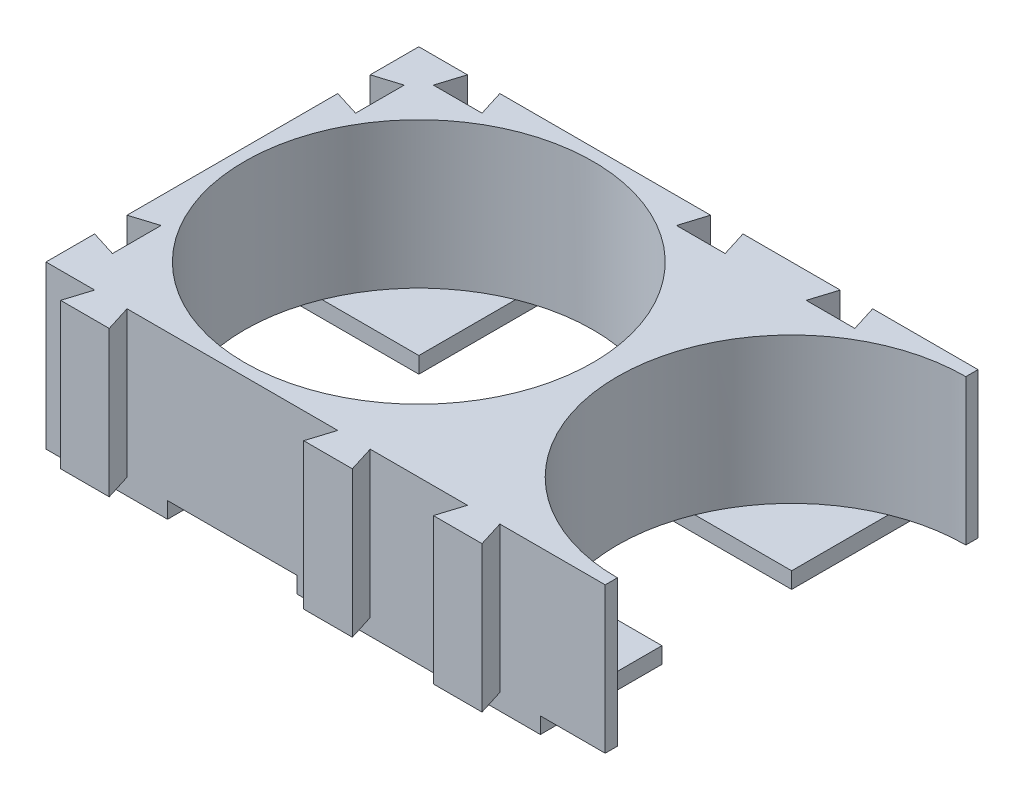
SolidWorks part; units mm, degrees
ref_plane "Front Plane" through (0, 0, 0) normal (0, 0, 1) x (1, 0, 0)
ref_plane "Top Plane" through (0, 0, 0) normal (0, 1, 0) x (1, 0, 0)
ref_plane "Right Plane" through (0, 0, 0) normal (1, 0, 0) x (0, 0, -1)
sketch "Sketch1" plane through (0, 0, 0) normal (0, 1, 0) x (1, 0, 0)
  line L1 (0, 0) -> (47.6, 0)
  line L2 (0, 0) -> (0, 24.6)
  line L3 (0, 24.6) -> (47.6, 24.6)
  line L4 (47.6, 0) -> (47.6, 24.6)
  dimension "D1" = 47.6
  dimension "D2" = 24.6
extrude "Boss-Extrude1" add sketch "Sketch1" along normal blind 10
sketch "Sketch2" plane through (0, 10, 0) normal (0, 1, 0) x (1, 0, 0)
  line L0 (0, -5.5) -> (0, 5.5) construction
  line L1 (47.6, 0) -> (47.6, 24.6) construction
  line L3 (47.6, 24.6) -> (0, 24.6) construction
  circle A0 centre (11.5, 13.1) radius 10.75
  circle A1 centre (34.5, 13.1) radius 10.75
  dimension "D1" = 21.5
  dimension "D2" = 21.5
  dimension "D3" = 23
  dimension "D4" = 11.5
  dimension "D5" = 13.1
  dimension "D6" = 11.5
extrude "Cut-Extrude1" cut sketch "Sketch2" against normal blind 9
sketch "Sketch3" plane through (0, 10, 0) normal (0, 1, 0) x (1, 0, 0)
  line L0 (0, 24.6) -> (0, -11.4) construction
  line L1 (0, -5.5) -> (0, 5.5) construction
  line L2 (47.6, 24.6) -> (0, 24.6) construction
  line L9 (3, 24.6) -> (2.5, 23)
  line L10 (2.5, 23) -> (5.5, 23)
  line L11 (5.5, 23) -> (5, 24.6)
  line L12 (5, 24.6) -> (3, 24.6)
  line L13 (18, 24.6) -> (17.5, 23)
  line L14 (17.5, 23) -> (20.5, 23)
  line L15 (20.5, 23) -> (20, 24.6)
  line L16 (20, 24.6) -> (18, 24.6)
  line L17 (26, 24.6) -> (25.5, 23)
  line L18 (25.5, 23) -> (28.5, 23)
  line L19 (28.5, 23) -> (28, 24.6)
  line L20 (28, 24.6) -> (26, 24.6)
  line L21 (41, 24.6) -> (40.5, 23)
  line L22 (40.5, 23) -> (43.5, 23)
  line L23 (43.5, 23) -> (43, 24.6)
  line L24 (43, 24.6) -> (41, 24.6)
  line L25 (0, 21.6) -> (1.6, 22.1)
  line L26 (1.6, 22.1) -> (1.6, 19.1)
  line L27 (1.6, 19.1) -> (0, 19.6)
  line L28 (0, 19.6) -> (0, 21.6)
  line L29 (0, 6.6) -> (1.6, 7.1)
  line L30 (1.6, 7.1) -> (1.6, 4.1)
  line L31 (1.6, 4.1) -> (0, 4.6)
  line L32 (0, 4.6) -> (0, 6.6)
  dimension "D1" = 2
  dimension "D2" = 3
  dimension "D3" = 0.5
  dimension "D4" = 1.6
  dimension "D5" = 3
  dimension "D6" = 13
  dimension "D7" = 2
  dimension "D8" = 3
  dimension "D9" = 0.5
  dimension "D10" = 1.6
  dimension "D11" = 6
  dimension "D12" = 2
  dimension "D13" = 3
  dimension "D14" = 0.5
  dimension "D15" = 1.6
  dimension "D16" = 13
  dimension "D17" = 2
  dimension "D18" = 3
  dimension "D19" = 0.5
  dimension "D20" = 1.6
  dimension "D21" = 3
  dimension "D22" = 2
  dimension "D23" = 0.5
  dimension "D24" = 1.6
  dimension "D25" = 3
  dimension "D26" = 3
  dimension "D27" = 2
  dimension "D28" = 0.5
  dimension "D29" = 1.6
  dimension "D30" = 13
extrude "Cut-Extrude2" cut sketch "Sketch3" against normal blind 9
sketch "Sketch5" plane through (0, 10, 0) normal (0, 1, 0) x (1, 0, 0)
  line L0 (-5.5, 0) -> (5.5, 0) construction
  line L1 (47.6, 24.6) -> (46, 24.6)
  line L2 (47.6, 24.6) -> (47.6, 0)
  line L3 (47.6, 0) -> (46, 0)
  line L4 (46, 24.6) -> (46, 0)
  dimension "D1" = 1.6
extrude "Cut-Extrude3" cut sketch "Sketch5" against normal blind 10
sketch "Sketch6" plane through (0, 10, 0) normal (0, 1, 0) x (1, 0, 0)
  line L0 (46, 24.6) -> (46, 0) construction
  line L1 (0, 0) -> (46, 0)
  line L2 (0, 0) -> (0, 1.6)
  line L3 (0, 1.6) -> (46, 1.6)
  line L4 (46, 0) -> (46, 1.6)
  dimension "D1" = 1.6
extrude "Cut-Extrude4" cut sketch "Sketch6" against normal blind 10
sketch "Sketch7" plane through (0, 10, 0) normal (0, 1, 0) x (1, 0, 0)
  line L0 (46, 21.6) -> (47.6, 22.1)
  line L1 (46, 24.6) -> (46, 1.6) construction
  line L2 (47.6, 22.1) -> (47.6, 19.1)
  line L3 (47.6, 19.1) -> (46, 19.6)
  line L4 (46, 19.6) -> (46, 21.6)
  line L9 (46, 6.6) -> (47.6, 7.1)
  line L10 (47.6, 7.1) -> (47.6, 4.1)
  line L11 (47.6, 4.1) -> (46, 4.6)
  line L12 (46, 4.6) -> (46, 6.6)
  line L13 (3, 1.6) -> (2.5, 0)
  line L14 (46, 1.6) -> (0, 1.6) construction
  line L15 (-5.5, 0) -> (5.5, 0) construction
  line L16 (2.5, 0) -> (5.5, 0)
  line L17 (5.5, 0) -> (5, 1.6)
  line L18 (5, 1.6) -> (3, 1.6)
  line L19 (0, -5.5) -> (0, 5.5) construction
  line L20 (18, 1.6) -> (17.5, 0)
  line L21 (17.5, 0) -> (20.5, 0)
  line L22 (20.5, 0) -> (20, 1.6)
  line L23 (20, 1.6) -> (18, 1.6)
  line L24 (26, 1.6) -> (25.5, 0)
  line L25 (25.5, 0) -> (28.5, 0)
  line L26 (28.5, 0) -> (28, 1.6)
  line L27 (28, 1.6) -> (26, 1.6)
  line L28 (41, 1.6) -> (40.5, 0)
  line L29 (40.5, 0) -> (43.5, 0)
  line L30 (43.5, 0) -> (43, 1.6)
  line L31 (43, 1.6) -> (41, 1.6)
  dimension "D1" = 3
  dimension "D2" = 2
  dimension "D3" = 0.5
  dimension "D4" = 1.6
  dimension "D5" = 3
  dimension "D6" = 13
  dimension "D7" = 2
  dimension "D8" = 3
  dimension "D9" = 0.5
  dimension "D10" = 1.6
  dimension "D11" = 3
  dimension "D12" = 2
  dimension "D13" = 3
  dimension "D14" = 0.5
  dimension "D15" = 1.6
  dimension "D16" = 2
  dimension "D17" = 3
  dimension "D18" = 0.5
  dimension "D19" = 1.6
  dimension "D20" = 13
  dimension "D21" = 2
  dimension "D22" = 3
  dimension "D23" = 0.5
  dimension "D24" = 6
  dimension "D25" = 2
  dimension "D26" = 3
  dimension "D27" = 0.5
  dimension "D28" = 13
extrude "Boss-Extrude2" add sketch "Sketch7" against normal blind 9
sketch "Sketch10" plane through (0, 0, 0) normal (0, -1, 0) x (1, 0, 0)
  line L0 (0, -5.5) -> (0, 5.5) construction
  line L1 (0, -9.1) -> (46, -9.1)
  line L2 (0, -9.1) -> (0, -17.1039)
  line L3 (0, -17.1039) -> (46, -17.1039)
  line L4 (46, -9.1) -> (46, -17.1039)
  line L5 (46, -24.6) -> (46, -1.6) construction
  line L7 (46, -1.6) -> (0, -1.6) construction
  dimension "D1" = 8.0039
  dimension "D2" = 7.5
extrude "Cut-Extrude5" cut sketch "Sketch10" against normal blind 1
sketch "Sketch11" plane through (0, 0, 0) normal (0, -1, 0) x (1, 0, 0)
  line L0 (46, -1.6) -> (0, -1.6) construction
  line L1 (7.5, -1.6) -> (15.5, -1.6)
  line L2 (7.5, -1.6) -> (7.5, -24.6)
  line L3 (7.5, -24.6) -> (15.5, -24.6)
  line L4 (15.5, -1.6) -> (15.5, -24.6)
  line L5 (46, -24.6) -> (0, -24.6) construction
  line L6 (0, -5.5) -> (0, 5.5) construction
  line L8 (30.5, -1.6) -> (38.5, -1.6)
  line L9 (30.5, -1.6) -> (30.5, -24.6)
  line L10 (30.5, -24.6) -> (38.5, -24.6)
  line L11 (38.5, -1.6) -> (38.5, -24.6)
  dimension "D1" = 8
  dimension "D2" = 7.5
  dimension "D3" = 8
  dimension "D4" = 7.5
extrude "Cut-Extrude6" cut sketch "Sketch11" against normal blind 1
sketch "Sketch12" plane through (0, 10, 0) normal (0, 1, 0) x (1, 0, 0)
  line L0 (41, 24.6) -> (28, 24.6) construction
  line L1 (34.5, 24.6) -> (47.8557, 24.6)
  line L2 (34.5, 24.6) -> (34.5, 0)
  line L3 (34.5, 0) -> (47.8557, 0)
  line L4 (47.8557, 24.6) -> (47.8557, 0)
  line L5 (-5.5, 0) -> (5.5, 0) construction
extrude "Cut-Extrude8" cut sketch "Sketch12" against normal blind 10 contours L4 L3 L2 L1
